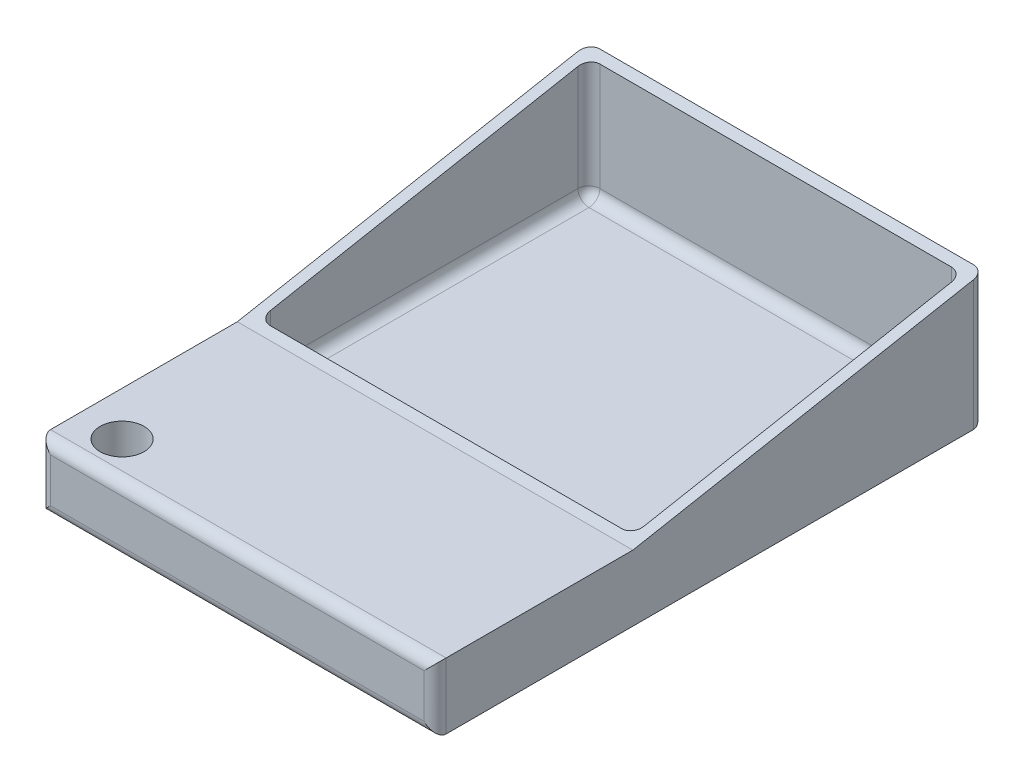
SolidWorks part; units mm, degrees
ref_plane "Front Plane" through (0, 0, 0) normal (0, 0, 1) x (1, 0, 0)
ref_plane "Top Plane" through (0, 0, 0) normal (0, 1, 0) x (1, 0, 0)
ref_plane "Right Plane" through (0, 0, 0) normal (1, 0, 0) x (0, 0, -1)
sketch "Sketch1" plane through (0, 0, 0) normal (1, 0, 0) x (0, 0, -1)
  line L0 (0, 0) -> (80, 0)
  line L1 (80, 0) -> (80, 30)
  line L2 (80, 30) -> (0, 15)
  line L3 (0, 15) -> (0, 0)
  dimension "D1" = 80
  dimension "D2" = 30
  dimension "D3" = 15
  dimension "D4" = 0
  dimension "D5" = 0
extrude "Boss-Extrude1" add sketch "Sketch1" along normal blind 90
shell "Shell1" thickness 2.5
sketch "Sketch2" plane through (0, 0, 0) normal (0, -1, 0) x (1, 0, 0)
  line L0 (90, 0) -> (90, -80) construction
  line L1 (0, 0) -> (90, 0)
  line L2 (0, 0) -> (0, 45)
  line L3 (0, 45) -> (90, 45)
  line L4 (90, 0) -> (90, 45)
  dimension "D1" = 45
  dimension "D2" = 0
extrude "Boss-Extrude2" add sketch "Sketch2" against normal up to vertex (15 mm away) up to point (0, 15, 0)
sketch "Sketch3" plane through (0, 0, 0) normal (0, -1, 0) x (1, 0, 0)
  line L1 (0, 45) -> (0, -80) construction
  point P0 (10, 36.22)
  dimension "D1" = 36.22
  dimension "D2" = 10
hole_wizard "Ø10.0mm Dowel Hole1" positions "Sketch3" profile "Sketch4" hole size "Ø10.0" standard "ANSI Metric" end condition up to next
sketch "Sketch4" plane through (10, 0, 36.22) normal (1, 0, 0) x (0, 0, -1)
  line L0 (0, 0) -> (0, 15)
  line L1 (0, 15) -> (5, 15)
  line L2 (5, 15) -> (5, 0)
  line L5 (5, 0) -> (0, 0)
  line L11 (0, -6.35) -> (0, 107.95) construction
  dimension "Thru Hole Dia." = 10
  dimension "Thru Hole Depth" = 15
fillet "Fillet1" radius 2.5 15 edges at (45, 2.5, -77.5) (87.5, 2.5, -40) (45, 2.5, -2.5) (2.5, 2.5, -40) (0, 7.5, 45) (45, 15, 45) (90, 7.5, 45) (45, 0, 45) (2.5, 8.9844, -2.5) (87.5, 8.9844, -2.5) (2.5, 16.0156, -77.5) (87.5, 16.0156, -77.5) (0, 15, -80) (90, 15, -80) (45, 0, -80)
